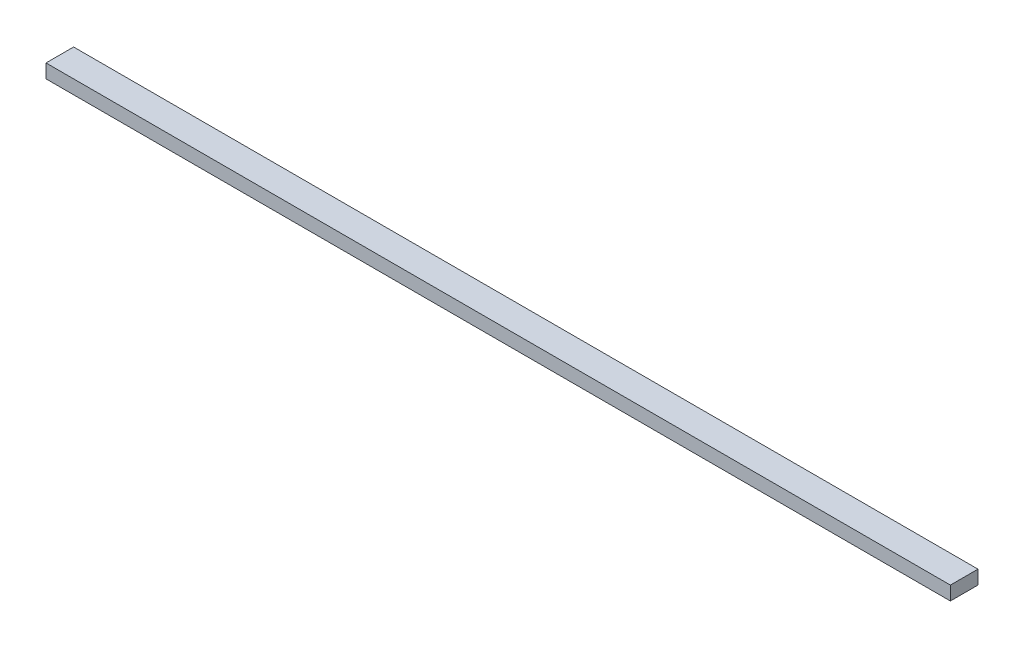
SolidWorks part; units mm, degrees
ref_plane "Plan de face" through (0, 0, 0) normal (0, 0, 1) x (1, 0, 0)
ref_plane "Plan de dessus" through (0, 0, 0) normal (0, 1, 0) x (1, 0, 0)
ref_plane "Plan de droite" through (0, 0, 0) normal (1, 0, 0) x (0, 0, -1)
sketch "Esquisse1" plane through (0, 0, 0) normal (0, 1, 0) x (1, 0, 0)
  line L1 (327.5, -10) -> (-327.5, -10)
  line L2 (327.5, -10) -> (327.5, 10)
  line L3 (327.5, 10) -> (-327.5, 10)
  line L4 (-327.5, -10) -> (-327.5, 10)
  line L5 (327.5, -10) -> (-327.5, 10) construction
  line L6 (327.5, 10) -> (-327.5, -10) construction
  point P0 (0, 0)
  dimension "D1" = 655
  dimension "D2" = 20
extrude "Boss.-Extru.1" add sketch "Esquisse1" along normal blind 10
sketch "Esquisse2" plane through (0, 0, 0) normal (0, -1, 0) x (1, 0, 0)
  line L1 (-350, 33.9378) -> (350, 33.9378)
  line L2 (-350, 33.9378) -> (-350, -33.9378)
  line L3 (-350, -33.9378) -> (350, -33.9378)
  line L4 (350, 33.9378) -> (350, -33.9378)
  line L5 (-350, 33.9378) -> (350, -33.9378) construction
  line L6 (-350, -33.9378) -> (350, 33.9378) construction
  point P0 (0, 0)
  dimension "D1" = 700
